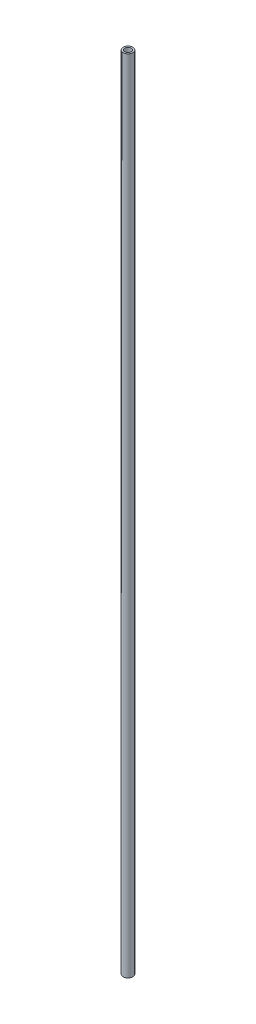
SolidWorks part; units mm, degrees
material "3.0205 (EN AW-1200)"
ref_plane "Ebene vorne" through (0, 0, 0) normal (0, 0, 1) x (1, 0, 0)
ref_plane "Ebene oben" through (0, 0, 0) normal (0, 1, 0) x (1, 0, 0)
ref_plane "Ebene rechts" through (0, 0, 0) normal (1, 0, 0) x (0, 0, -1)
sketch "Skizze1" plane through (0, 0, 0) normal (0, 1, 0) x (1, 0, 0)
  circle A0 centre (0, 0) radius 3
  circle A1 centre (0, 0) radius 2
  dimension "D1" = 1
  dimension "D2" = 6
extrude "Aufsatz-Linear austragen1" add sketch "Skizze1" along normal mid plane 500
